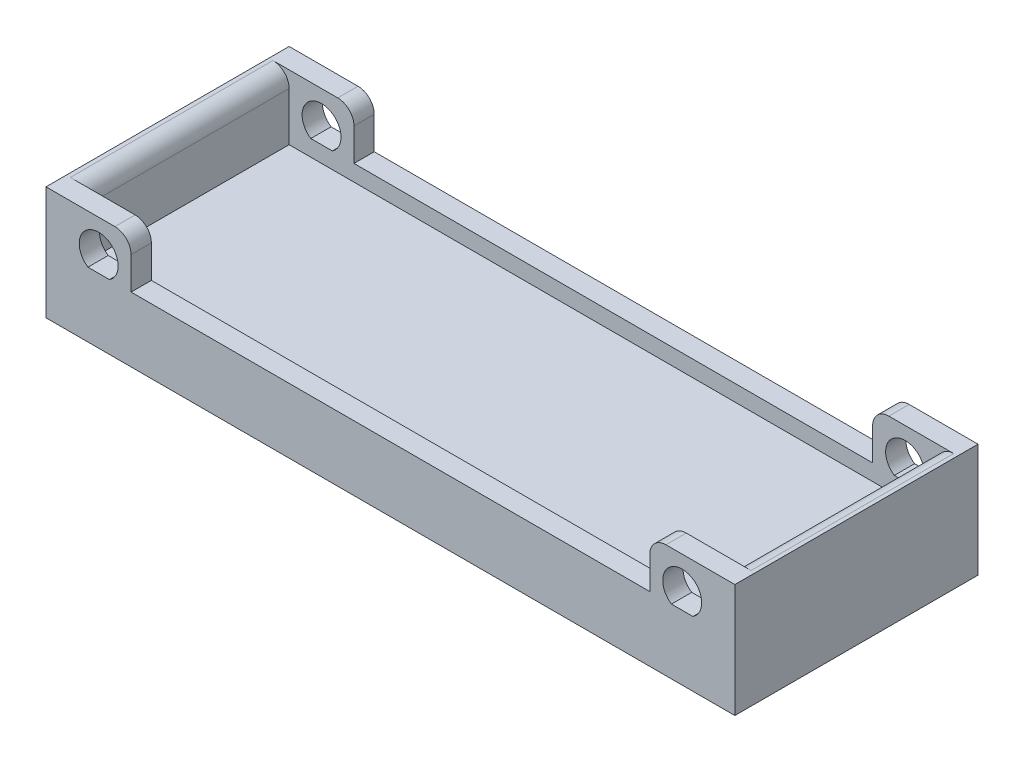
SolidWorks part; units mm, degrees
ref_plane "Front Plane" through (0, 0, 0) normal (0, 0, 1) x (1, 0, 0)
ref_plane "Top Plane" through (0, 0, 0) normal (0, 1, 0) x (1, 0, 0)
ref_plane "Right Plane" through (0, 0, 0) normal (1, 0, 0) x (0, 0, -1)
sketch "Sketch1" plane through (0, 0, 0) normal (0, 0, 1) x (1, 0, 0)
  line L1 (42.5, -4) -> (-42.5, -4)
  line L2 (42.5, -4) -> (42.5, 4)
  line L3 (42.5, 4) -> (-42.5, 4)
  line L4 (-42.5, -4) -> (-42.5, 4)
  line L5 (42.5, -4) -> (-42.5, 4) construction
  line L6 (42.5, 4) -> (-42.5, -4) construction
  point P0 (0, 0)
  dimension "D1" = 8
  dimension "D2" = 85
extrude "Boss-Extrude1" add sketch "Sketch1" along normal blind 30
sketch "Sketch2" plane through (0, 4, 0) normal (0, 1, 0) x (1, 0, 0)
  line L0 (-42.5, -30) -> (-42.5, 0) construction
  line L1 (40, -27.5) -> (-40, -27.5)
  line L2 (40, -27.5) -> (40, -2.5)
  line L3 (40, -2.5) -> (-40, -2.5)
  line L4 (-40, -27.5) -> (-40, -2.5)
  line L5 (40, -27.5) -> (-40, -2.5) construction
  line L6 (40, -2.5) -> (-40, -27.5) construction
  point P0 (0, -15)
  point P8 (-42.5, -15)
  dimension "D1" = 80
  dimension "D2" = 25
  dimension "D3" = 0
  dimension "D4" = 0
extrude "Cut-Extrude1" cut sketch "Sketch2" against normal blind 2
sketch "Sketch3" plane through (0, 4, 0) normal (0, 1, 0) x (1, 0, 0)
  line L0 (42.5, -30) -> (-42.5, -30) construction
  line L1 (-42.5, 0) -> (-32, 0)
  line L2 (-42.5, 0) -> (-42.5, -30)
  line L3 (-42.5, -30) -> (-32, -30)
  line L4 (-32, 0) -> (-32, -30)
  line L13 (-40, -2.5) -> (-40, -27.5)
  line L14 (-40, -27.5) -> (40, -27.5)
  line L15 (40, -27.5) -> (40, -2.5)
  line L16 (40, -2.5) -> (-40, -2.5)
  line L17 (-40, -2.5) -> (-40, -27.5)
  line L18 (-40, -27.5) -> (40, -27.5)
  line L19 (40, -27.5) -> (40, -2.5)
  line L20 (40, -2.5) -> (-40, -2.5)
  line M9 (40, -27.5) -> (-40, -27.5)
  line M10 (-40, -27.5) -> (-40, -2.5)
  line M11 (-40, -2.5) -> (40, -2.5)
  line M13 (42.5, 0) -> (-42.5, 0)
  line M14 (-42.5, 0) -> (-42.5, -30)
  line M15 (-42.5, -30) -> (42.5, -30)
  dimension "D2" = 8
  dimension "D1" = 0
extrude "Boss-Extrude3" add sketch "Sketch3" along normal blind 6 contours L4 M13 M14 M15 M9 M10 M11
sketch "Sketch4" plane through (0, 0, 30) normal (0, 0, 1) x (1, 0, 0)
  point P0 (-36, 6)
  dimension "D1" = 4
  dimension "D2" = 4
hole_wizard "M4 Clearance Hole1" positions "Sketch5" profile "Sketch6" hole size "M4" standard "ANSI Metric" end condition through all
sketch "Sketch5" plane through (0, 0, 30) normal (0, 0, 1) x (1, 0, 0)
  point P0 (-36, 6)
sketch "Sketch6" plane through (-36, 6, 30) normal (1, 0, 0) x (0, -1, 0)
  line L0 (0, 0) -> (0, 30)
  line L1 (0, 30) -> (2.4, 30)
  line L2 (2.4, 30) -> (2.4, 0)
  line L5 (2.4, 0) -> (0, 0)
  line L11 (0, -6.35) -> (0, 107.95) construction
  dimension "Thru Hole Dia." = 4.8
  dimension "Thru Hole Depth" = 30
fillet "Fillet1" radius 2 3 edges at (-40, 10, 15) (-32, 10, 1.25) (-32, 10, 28.75)
mirror "Mirror1" about plane through (0, 0, 0) normal (1, 0, 0) of bodies 105
